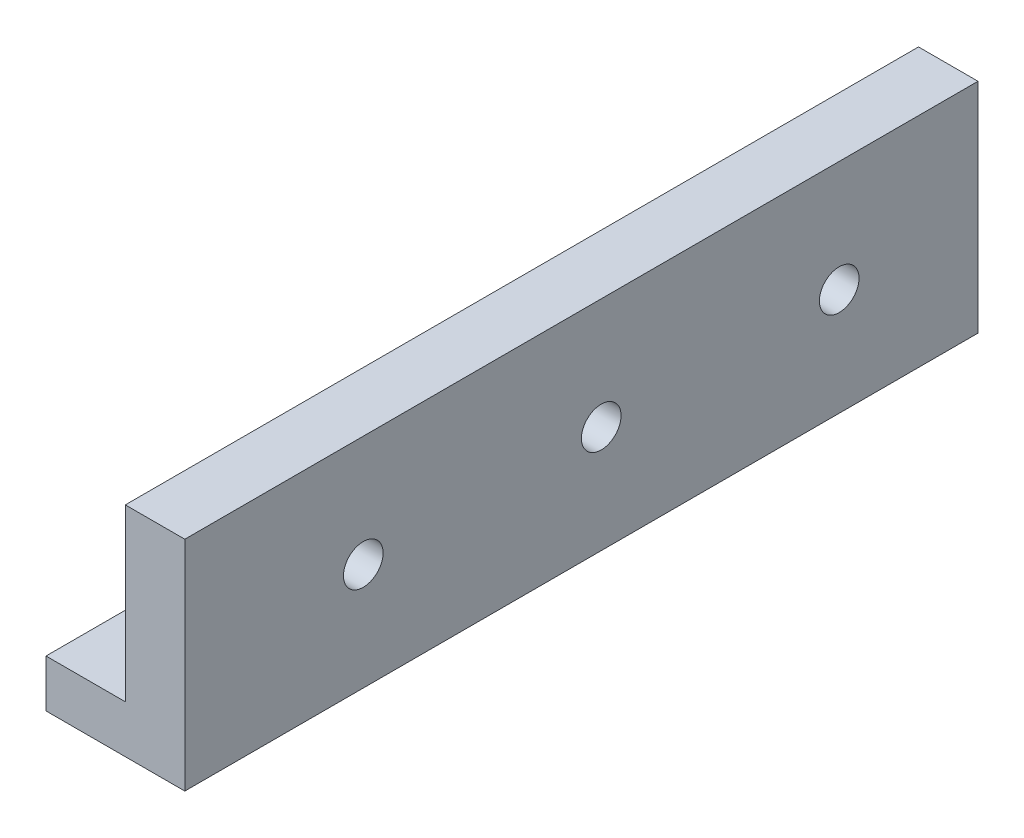
SolidWorks part; units mm, degrees
ref_plane "前基準面" through (0, 0, 0) normal (0, 0, 1) x (1, 0, 0)
ref_plane "上基準面" through (0, 0, 0) normal (0, 1, 0) x (1, 0, 0)
ref_plane "右基準面" through (0, 0, 0) normal (1, 0, 0) x (0, 0, -1)
sketch "草圖1" plane through (0, 0, 0) normal (0, 0, 1) x (1, 0, 0)
  line L0 (-5.0196, 208.8052) -> (-5.0196, 165.8052)
  line L2 (-5.0196, 165.8052) -> (-25.0196, 165.8052)
  line L3 (-25.0196, 165.8052) -> (-25.0196, 153.8052)
  line L4 (-25.0196, 153.8052) -> (9.9804, 153.8052)
  line L5 (9.9804, 153.8052) -> (9.9804, 208.8052)
  line L6 (9.9804, 208.8052) -> (-5.0196, 208.8052)
  dimension "D1" = 35
  dimension "D2" = 12
  dimension "D3" = 55
  dimension "D4" = 15
extrude "填料-伸長1" add sketch "草圖1" against normal blind 200
sketch "草圖2" plane through (9.9804, 0, 0) normal (1, 0, 0) x (0, 0, -1)
  line L2 (200, 153.8052) -> (0, 153.8052) construction
  line L3 (200, 153.8052) -> (200, 208.8052) construction
  circle A0 centre (45, 180.8052) radius 5
  circle A1 centre (105, 180.8052) radius 5
  circle A2 centre (165, 180.8052) radius 5
  point P12 (-96.2796, 195.9341)
  dimension "D1" = 10
  dimension "D2" = 10
  dimension "D3" = 10
  dimension "D7" = 35
  dimension "D8" = 27
  dimension "D9" = 27
  dimension "D4" = 60
  dimension "D5" = 60
extrude "除料-伸長1" cut sketch "草圖2" against normal up to next and the other way through all
